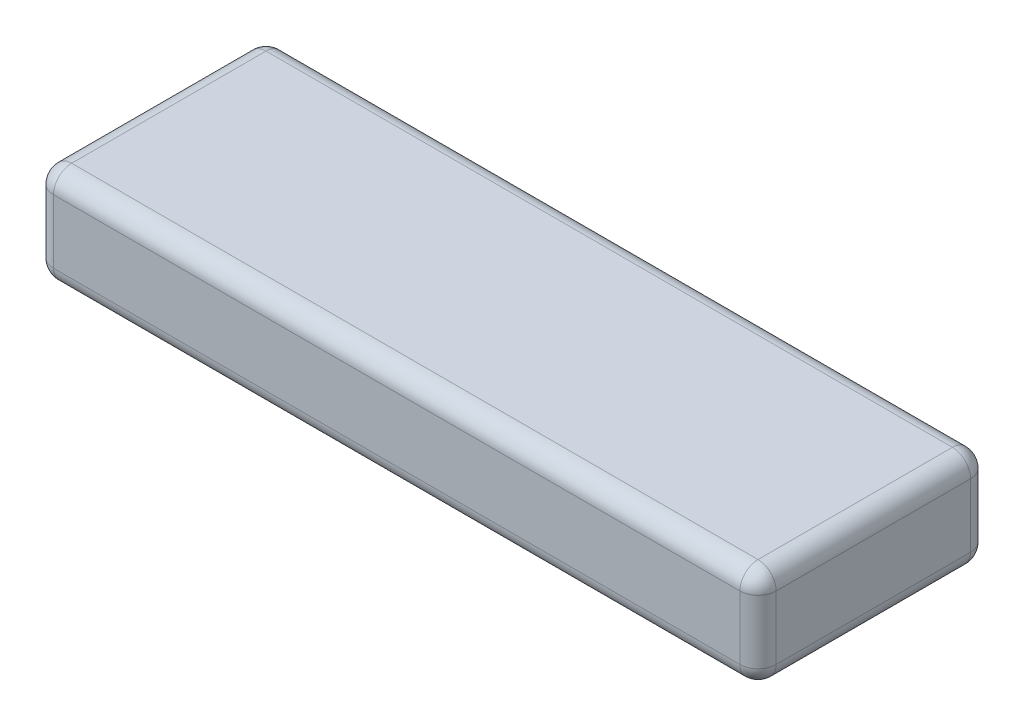
SolidWorks part; units mm, degrees
ref_plane "Front Plane" through (0, 0, 0) normal (0, 0, 1) x (1, 0, 0)
ref_plane "Top Plane" through (0, 0, 0) normal (0, 1, 0) x (1, 0, 0)
ref_plane "Right Plane" through (0, 0, 0) normal (1, 0, 0) x (0, 0, -1)
sketch "Sketch1" plane through (0, 0, 0) normal (0, 1, 0) x (1, 0, 0)
  line L1 (-29.845, -9.525) -> (29.845, -9.525)
  line L2 (-29.845, -9.525) -> (-29.845, 9.525)
  line L3 (-29.845, 9.525) -> (29.845, 9.525)
  line L4 (29.845, -9.525) -> (29.845, 9.525)
  line L5 (-29.845, -9.525) -> (29.845, 9.525) construction
  line L6 (-29.845, 9.525) -> (29.845, -9.525) construction
  point P0 (0, 0)
  dimension "D1" = 59.69
  dimension "D2" = 19.05
extrude "Boss-Extrude1" add sketch "Sketch1" along normal blind 8.255
fillet "Fillet1" radius 1.5 12 edges at (-29.845, 4.1275, -9.525) (-29.845, 4.1275, 9.525) (0, 0, -9.525) (-29.845, 0, 0) (0, 0, 9.525) (29.845, 4.1275, 9.525) (29.845, 4.1275, -9.525) (29.845, 0, 0) (0, 8.255, 9.525) (-29.845, 8.255, 0) (0, 8.255, -9.525) (29.845, 8.255, 0)
